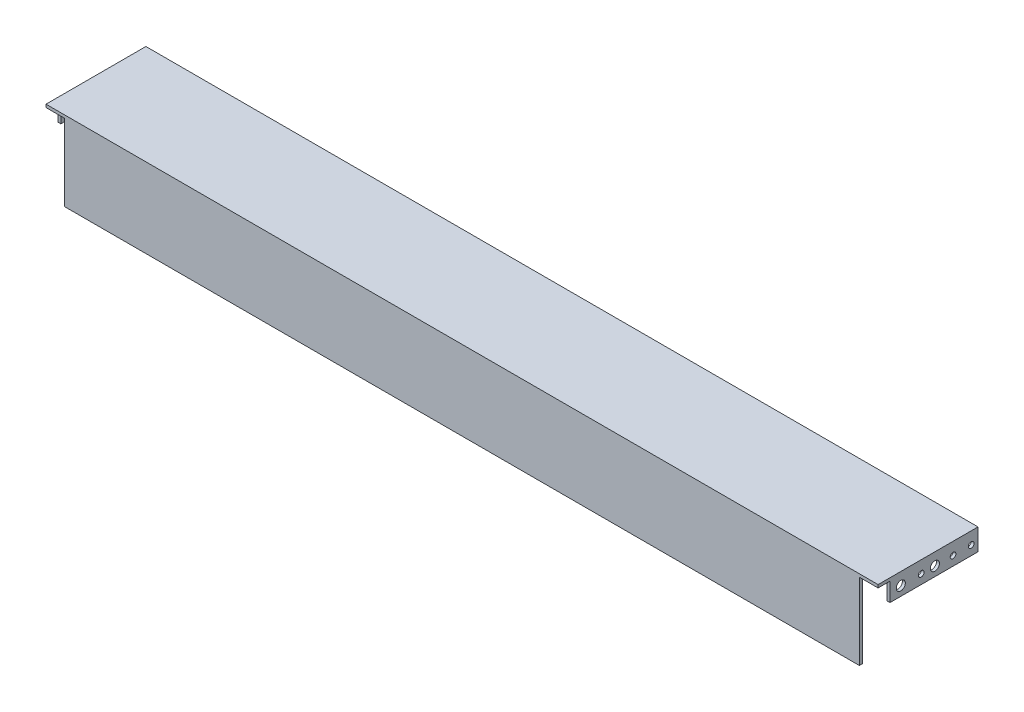
SolidWorks part; units mm, degrees
ref_plane "Front Plane" through (0, 0, 0) normal (0, 0, 1) x (1, 0, 0)
ref_plane "Top Plane" through (0, 0, 0) normal (0, 1, 0) x (1, 0, 0)
ref_plane "Right Plane" through (0, 0, 0) normal (1, 0, 0) x (0, 0, -1)
sketch "Sketch1" plane through (0, 0, 0) normal (0, 0, 1) x (1, 0, 0)
  line L1 (-350, 35) -> (350, 35)
  line L2 (-350, 35) -> (-350, -35)
  line L3 (-350, -35) -> (350, -35)
  line L4 (350, 35) -> (350, -35)
  line L5 (-350, 35) -> (350, -35) construction
  line L6 (-350, -35) -> (350, 35) construction
  point P0 (0, 0)
extrude "Boss-Extrude1" add sketch "Sketch1" against normal blind 2.6
sketch "Sketch2" plane through (0, 35, 0) normal (0, 1, 0) x (1, 0, 0)
  line L0 (-366.5, 0) -> (366.5, 0)
  line L2 (366.5, 0) -> (366.5, 88)
  line L3 (366.5, 88) -> (-366.5, 88)
  line L4 (-366.5, 0) -> (-366.5, 88)
  point P0 (0, 0)
extrude "Boss-Extrude2" add sketch "Sketch2" against normal blind 2.6
sketch "Sketch3" plane through (-366.5, 0, 0) normal (-1, 0, 0) x (0, 0, 1)
  line L0 (-88, 32.4) -> (-10.5, 32.4)
  line L1 (-88, 24.2) -> (-82, 24.2) construction
  line L2 (-88, 32.4) -> (-88, 16)
  line L3 (-88, 16) -> (-10.5, 16)
  line L4 (-10.5, 32.4) -> (-10.5, 16)
  line L5 (-88, 32.4) -> (0, 32.4) construction
  circle A0 centre (-82, 24.2) radius 2.5
  circle A1 centre (-66, 24.2) radius 2.5
  circle A2 centre (-50, 24.2) radius 4
  circle A3 centre (-38, 24.2) radius 2.5
  circle A4 centre (-20, 24.2) radius 4
extrude "Boss-Extrude3" add sketch "Sketch3" against normal blind 2.6
sketch "Sketch4" plane through (366.5, 0, 0) normal (1, 0, 0) x (0, 0, -1)
  line L4 (88, 32.4) -> (10.5, 32.4)
  line L5 (10.5, 32.4) -> (10.5, 16)
  line L6 (10.5, 16) -> (88, 16)
  line L7 (88, 16) -> (88, 32.4)
  line L8 (88, 32.4) -> (10.5, 32.4)
  line L9 (10.5, 32.4) -> (10.5, 16)
  line L10 (10.5, 16) -> (88, 16)
  line L11 (88, 16) -> (88, 32.4)
  circle A1 centre (38, 24.2) radius 2.5
  circle A2 centre (38, 24.2) radius 2.5
  circle A3 centre (50, 24.2) radius 4
  circle A4 centre (50, 24.2) radius 4
  circle A5 centre (66, 24.2) radius 2.5
  circle A6 centre (66, 24.2) radius 2.5
  circle A7 centre (82, 24.2) radius 2.5
  circle A8 centre (82, 24.2) radius 2.5
  circle A9 centre (20, 24.2) radius 4
  circle A10 centre (20, 24.2) radius 4
  dimension "D1" = 0
  dimension "D2" = 0
  dimension "D3" = 0
  dimension "D4" = 0
  dimension "D5" = 0
  dimension "D6" = 0
extrude "Boss-Extrude4" add sketch "Sketch4" against normal blind 2.6
